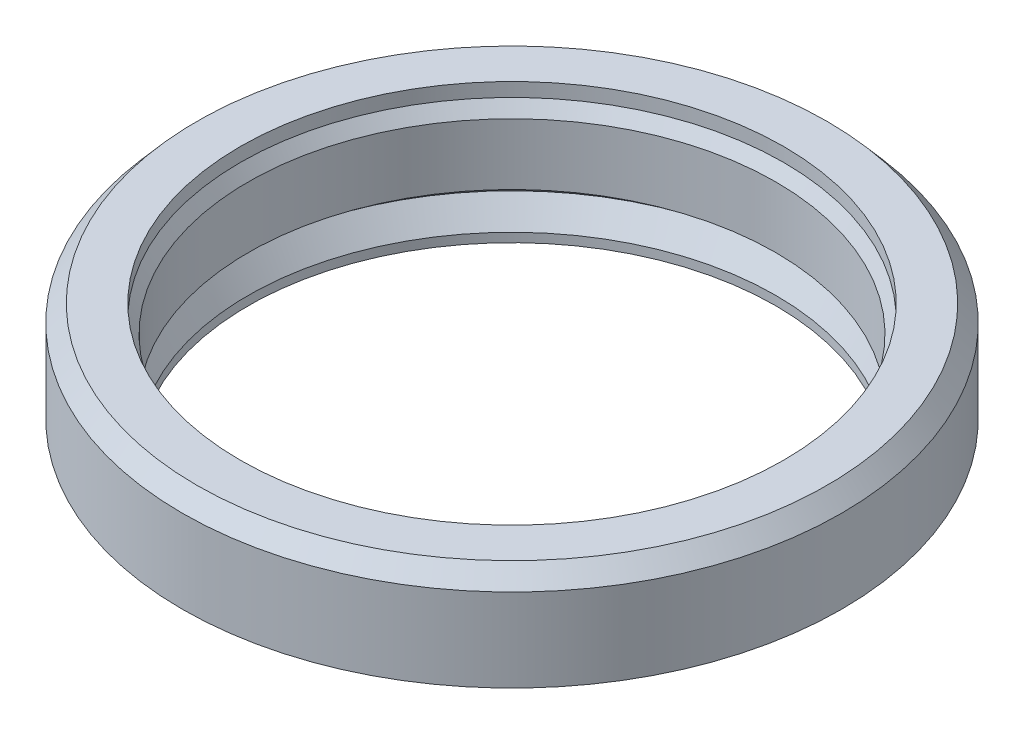
SolidWorks part; units mm, degrees
ref_plane "Alzado" through (0, 0, 0) normal (0, 0, 1) x (1, 0, 0)
ref_plane "Planta" through (0, 0, 0) normal (0, 1, 0) x (1, 0, 0)
ref_plane "Vista lateral" through (0, 0, 0) normal (1, 0, 0) x (0, 0, -1)
sketch "Croquis1" plane through (0, 0, 0) normal (0, 0, 1) x (1, 0, 0)
  line L11 (0, 26.0987) -> (0, -21.2147) construction
  line L12 (-8, 1.873) -> (-8, 3.7306)
  line L13 (-8, 1.873) -> (-8.4746, 1.5034)
  line L15 (-9.9996, 1.5034) -> (-9.9996, 4.0263)
  line L16 (-9.9996, 4.0263) -> (-9.559, 4.5393)
  line L19 (-8.4746, 1.5034) -> (-8, 0.7494)
  line L20 (-8.7997, 4.5393) -> (8.8003, 4.5393) construction
  line L21 (-8, 18.1902) -> (-8, -14.4442) construction
  line L22 (-8, 0.7494) -> (-8, 0.4755)
  line L23 (-8, 3.7306) -> (-8.2403, 4.1203)
  line L24 (-8.2403, 4.1203) -> (-8.2403, 4.5393)
  line L25 (-8.2403, 4.5393) -> (-9.559, 4.5393)
  line L26 (-8, 0.4755) -> (-8.2501, 0.4755)
  line L29 (-9.9996, 1.5034) -> (-8.8971, 1.5034)
  line L30 (-8.8971, 1.5034) -> (-8.2501, 0.4755)
  dimension "D1" = 8
revolve "Revolución1" add sketch "Croquis1" angle 360 about L11
fillet "Redondeo1" radius 0.5 1 edges at (0, 1.5034, 8.8971)
